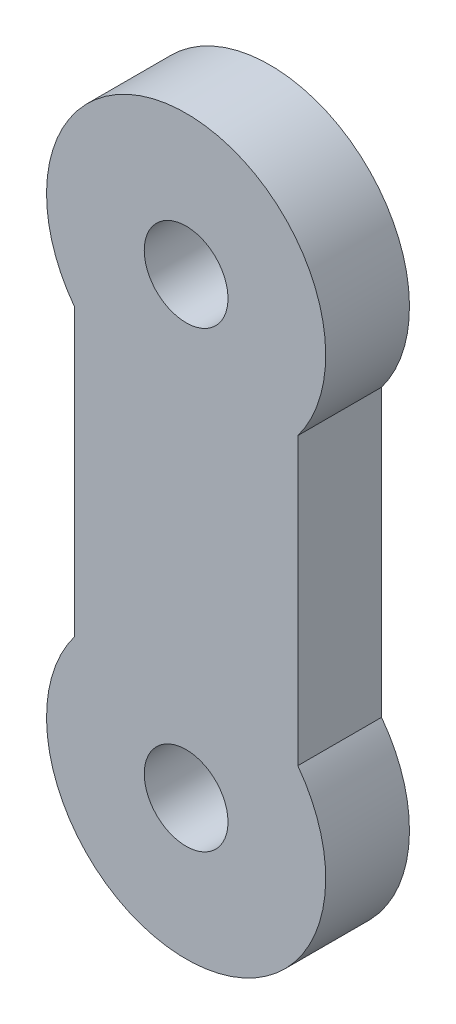
SolidWorks part; units mm, degrees
material "Thornel Mat VMA"
ref_plane "前视基准面" through (0, 0, 0) normal (0, 0, 1) x (1, 0, 0)
ref_plane "上视基准面" through (0, 0, 0) normal (0, 1, 0) x (1, 0, 0)
ref_plane "右视基准面" through (0, 0, 0) normal (1, 0, 0) x (0, 0, -1)
sketch "草图1" plane through (0, 0, 0) normal (0, 0, 1) x (1, 0, 0)
  line L1 (4, -8.12) -> (-4, -8.12)
  line L2 (4, -8.12) -> (4, 8.12)
  line L3 (4, 8.12) -> (-4, 8.12)
  line L4 (-4, -8.12) -> (-4, 8.12)
  line L5 (4, -8.12) -> (-4, 8.12) construction
  line L6 (4, 8.12) -> (-4, -8.12) construction
  circle A0 centre (0, 8.12) radius 5
  circle A1 centre (0, -8.12) radius 5
  point P0 (0, 0)
  dimension "D3" = 10
  dimension "D4" = 10
  dimension "D1" = 16.24
  dimension "D2" = 8
extrude "凸台-拉伸1" add sketch "草图1" along normal blind 3 contours L2 A0 L4 L3 | A1 L2 A0 L4 | L4 A0 L2 L3 | L2 A1 L4 L1 | L4 A1 L2 L1
sketch "草图2" plane through (0, 0, 0) normal (0, 0, -1) x (-1, 0, 0)
  line L0 (-9.3302, 0) -> (12.057, 0) construction
  circle A0 centre (0, 8.12) radius 1.5
  circle A1 centre (0, -8.12) radius 1.5
  dimension "D1" = 3
  dimension "D2" = 8.12
extrude "切除-拉伸1" cut sketch "草图2" against normal through all
